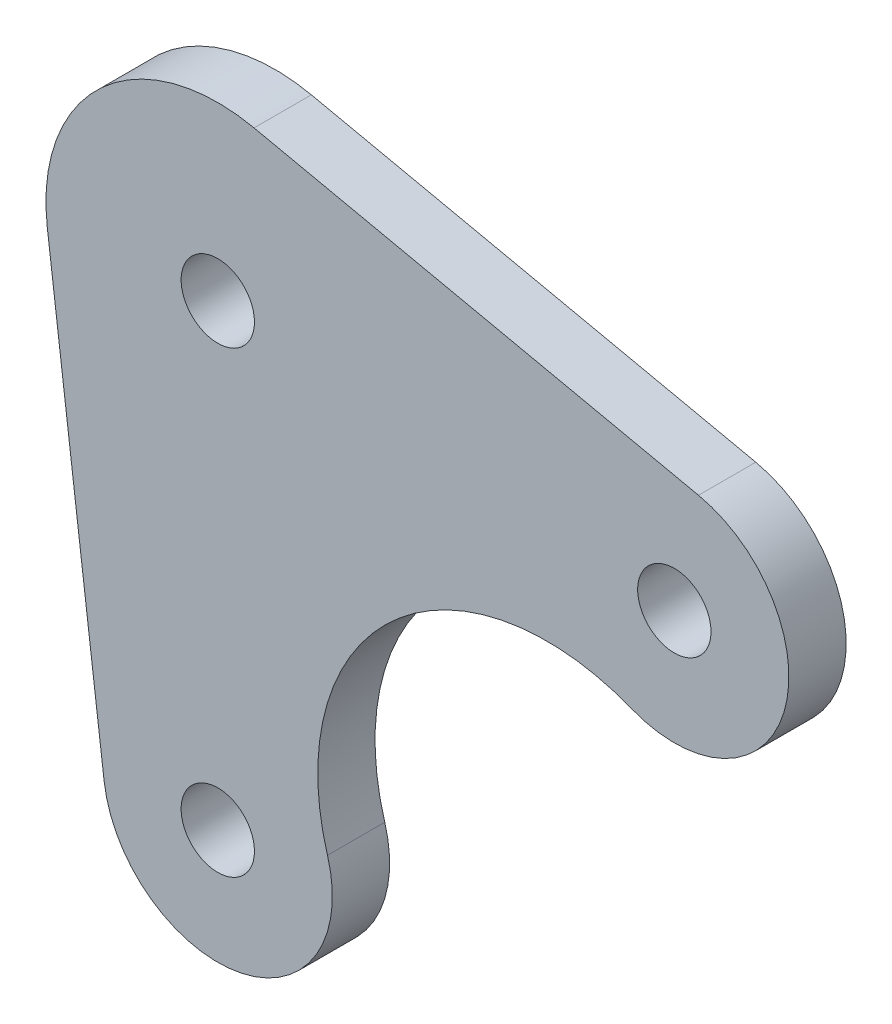
SolidWorks part; units mm, degrees
ref_plane "Front Plane" through (0, 0, 0) normal (0, 0, 1) x (1, 0, 0)
ref_plane "Top Plane" through (0, 0, 0) normal (0, 1, 0) x (1, 0, 0)
ref_plane "Right Plane" through (0, 0, 0) normal (1, 0, 0) x (0, 0, -1)
sketch "Sketch1" plane through (0, 0, 0) normal (0, 0, 1) x (1, 0, 0)
  line L0 (0, -25.4) -> (0, 0) construction
  line L1 (0, 0) -> (25.3033, -2.2138) construction
  line L2 (-6.3002, -26.1937) -> (-9.4503, -1.1906)
  line L3 (2.0097, 9.3106) -> (26.6432, 3.9933)
  circle A0 centre (0, 0) radius 2.032
  circle A1 centre (25.3033, -2.2138) radius 2.032
  circle A2 centre (0, -25.4) radius 2.032
  arc A3 (2.0097, 9.3106) -> (-9.4503, -1.1906) centre (0, 0) ccw
  arc A4 (-6.3002, -26.1937) -> (6.0802, -23.5687) centre (0, -25.4) ccw
  arc A5 (26.6432, 3.9933) -> (22.9491, -8.1112) centre (25.3033, -2.2138) cw
  arc A6 (22.9491, -8.1112) -> (6.0802, -23.5687) centre (18.2406, -19.9061) ccw
  point P15 (0, 0)
  point P16 (0, 0)
  dimension "D4" = 4.064
  dimension "D5" = 9.525
  dimension "D6" = 6.35
  dimension "D7" = 6.35
  dimension "D8" = 12.7
  dimension "D1" = 25.4
  dimension "D2" = 25.4
  dimension "D3" = 85
extrude "Boss-Extrude1" add sketch "Sketch1" along normal blind 3.175
